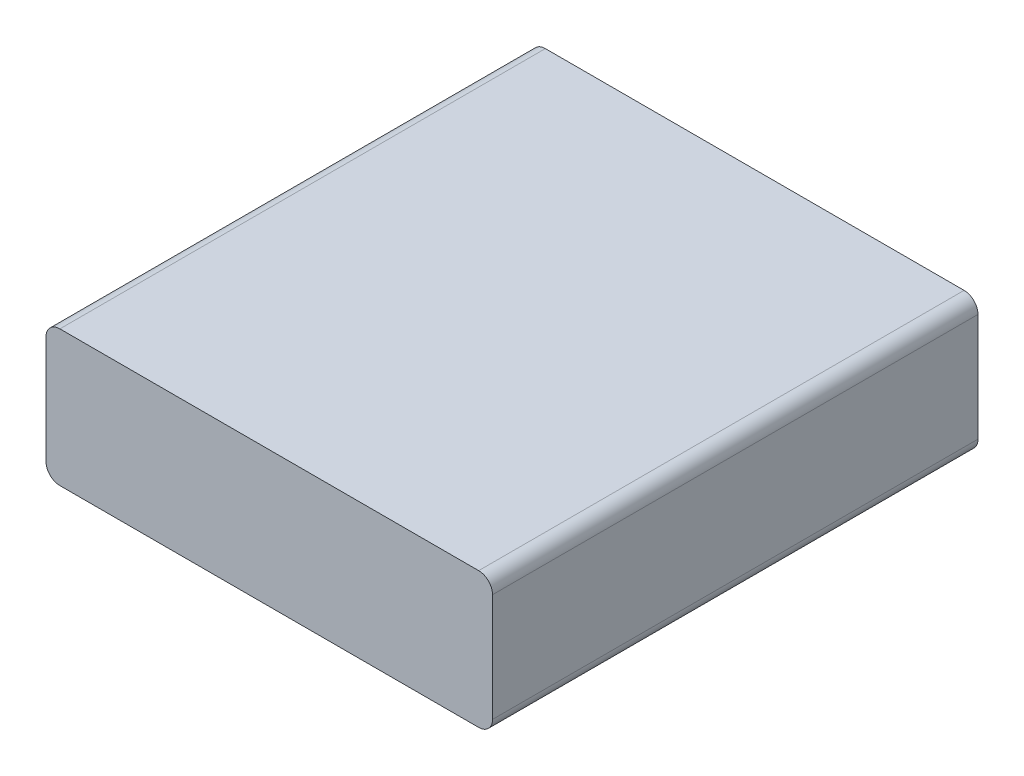
SolidWorks part; units mm, degrees
ref_plane "Front Plane" through (0, 0, 0) normal (0, 0, 1) x (1, 0, 0)
ref_plane "Top Plane" through (0, 0, 0) normal (0, 1, 0) x (1, 0, 0)
ref_plane "Right Plane" through (0, 0, 0) normal (1, 0, 0) x (0, 0, -1)
sketch "Sketch1" plane through (0, 0, 0) normal (0, 0, 1) x (1, 0, 0)
  line L1 (-32.15, 9.775) -> (32.15, 9.775)
  line L2 (-32.15, 9.775) -> (-32.15, -9.775)
  line L3 (-32.15, -9.775) -> (32.15, -9.775)
  line L4 (32.15, 9.775) -> (32.15, -9.775)
  line L5 (-32.15, 9.775) -> (32.15, -9.775) construction
  line L6 (-32.15, -9.775) -> (32.15, 9.775) construction
  point P0 (0, 0)
  dimension "D1" = 64.3
  dimension "D2" = 19.55
extrude "Body" add sketch "Sketch1" along normal blind 69.9
fillet "Fillet1" radius 2 4 edges at (32.15, -9.775, 34.95) (-32.15, -9.775, 34.95) (-32.15, 9.775, 34.95) (32.15, 9.775, 34.95)
